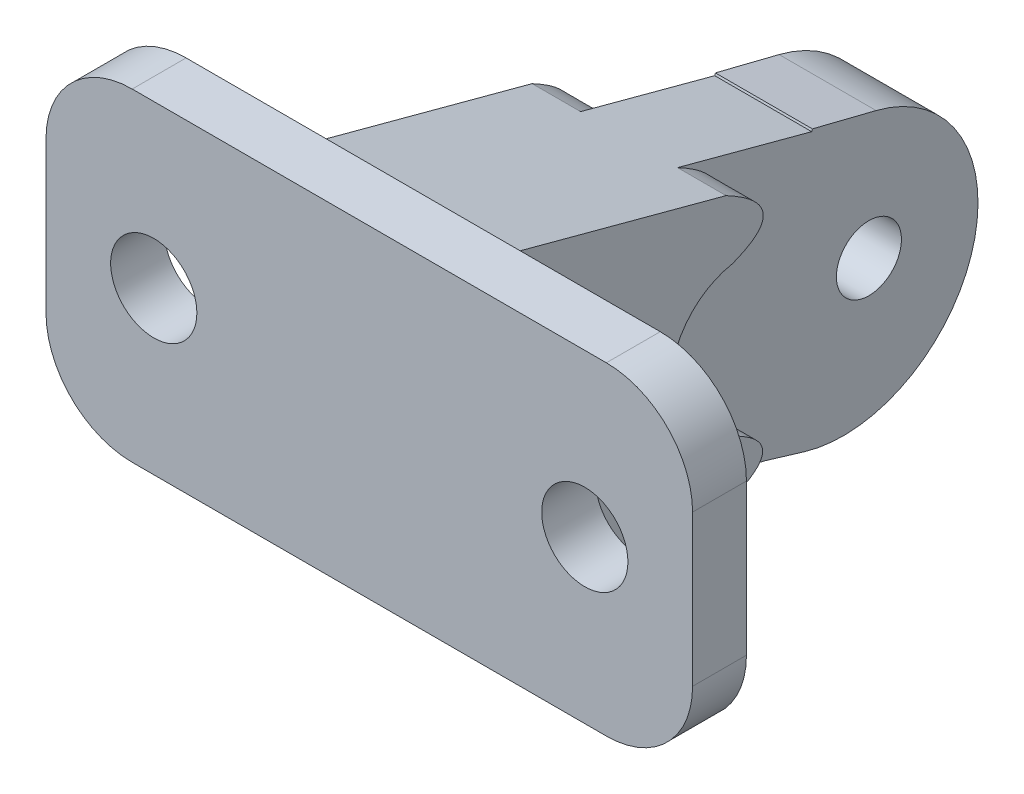
SolidWorks part; units mm, degrees
ref_plane "Front Plane" through (0, 0, 0) normal (0, 0, 1) x (1, 0, 0)
ref_plane "Top Plane" through (0, 0, 0) normal (0, 1, 0) x (1, 0, 0)
ref_plane "Right Plane" through (0, 0, 0) normal (1, 0, 0) x (0, 0, -1)
sketch "Sketch6" plane through (0, 0, 0) normal (0, 0, 1) x (1, 0, 0)
  line L0 (-20, 0) -> (20, 0) construction
  line L1 (-30, 15) -> (30, 15)
  line L2 (-30, 15) -> (-30, -15)
  line L3 (-30, -15) -> (30, -15)
  line L4 (30, 15) -> (30, -15)
  line L5 (-30, 15) -> (30, -15) construction
  line L6 (-30, -15) -> (30, 15) construction
  circle A2 centre (-20, 0) radius 4
  circle A3 centre (20, 0) radius 4
  point P0 (0, 0)
  dimension "D6" = 8
  dimension "D7" = 8
  dimension "D1" = 60
  dimension "D2" = 30
  dimension "D3" = 40
  dimension "D4" = 10
  dimension "D5" = 10
extrude "Boss-Extrude1" add sketch "Sketch6" along normal blind 5
fillet "Fillet3" radius 8 4 edges at (-30, -15, 2.5) (-30, 15, 2.5) (30, -15, 2.5) (30, 15, 2.5)
sketch "Sketch8" plane through (0, 0, 0) normal (0, 0, -1) x (-1, 0, 0)
  line L0 (-22, 15) -> (22, 15) construction
  line L1 (-9, 15) -> (9, 15)
  line L2 (-9, 15) -> (-9, -15)
  line L3 (-9, -15) -> (9, -15)
  line L4 (9, 15) -> (9, -15)
  line L5 (22, -15) -> (-22, -15) construction
  line L6 (-30, -7) -> (-30, 7) construction
  line L7 (30, 7) -> (30, -7) construction
  dimension "D1" = 21
  dimension "D2" = 21
  dimension "D3" = 18
extrude "Boss-Extrude2" add sketch "Sketch8" along normal blind 45
sketch "Sketch10" plane through (-9, 0, 0) normal (-1, 0, 0) x (0, 0, 1)
  line L0 (0, 15) -> (-45, 2.9423)
  line L1 (-45, -15) -> (-45, 15) construction
  line L2 (-45, 2.9423) -> (-45, 15)
  line L3 (-45, 15) -> (0, 15)
  dimension "D1" = 15
extrude "Cut-Extrude1" cut sketch "Sketch10" against normal blind 20
sketch "Sketch13" plane through (-9, 0, 0) normal (-1, 0, 0) x (0, 0, 1)
  line L0 (0, -32.8637) -> (-40, -32.8637) construction
  line L1 (0, -15) -> (0, -38.052) construction
  line L2 (-40, -32.8637) -> (-40, 12.6407) construction
  dimension "D1" = 40
  dimension "D2" = 0
sketch "Sketch15" plane through (-9, 0, 0) normal (-1, 0, 0) x (0, 0, 1)
  line L1 (-20.9686, -10.424) -> (-20.9686, -15) construction
  line L2 (-45, -15) -> (0, -15) construction
  line L3 (-45, 2.9423) -> (0, 15) construction
  line L4 (-19.1059, 9.8806) -> (0, 15)
  line L5 (0, 15) -> (0, -15)
  line L6 (0, -15) -> (-19.1059, -15)
  arc A2 (-18.8147, -9.4319) -> (-19.2388, 4.0114) centre (-20.9686, -2.7715) ccw
  spline S0 degree 2 poles (-19.1059, 9.8806) (-26.0968, 5.898) (-18.824, 3.8919) knots 0 0 0 1 1 1
  spline S1 degree 3 poles (-19.1059, -15) (-23.7374, -13.111) (-23.6404, -11.2549) (-18.8147, -9.4319) knots 0 0 0 0 0.967848 0.967848 0.967848 0.967848
  dimension "D1" = 14
sketch "Sketch17" plane through (-9, 0, 0) normal (-1, 0, 0) x (0, 0, 1)
  line L0 (-19.1059, 9.8806) -> (-33.795, 5.9447)
  line L1 (-45, 2.9423) -> (0, 15) construction
  line L2 (-33.795, 5.9447) -> (-33.1128, -15)
  line L3 (-45, -15) -> (0, -15) construction
  line L4 (-33.1128, -15) -> (-19.1059, -15)
  arc A0 (-19.3961, -9.5926) -> (-19.7213, 4.1165) centre (-20.9686, -2.7715) ccw
  spline S0 degree 2 poles (-19.1059, 9.8806) (-25.6883, 6.3887) (-19.7213, 4.1165) knots 0 0 0 1 1 1
  spline S1 degree 2 poles (-19.3961, -9.5926) (-25.7463, -12.5412) (-19.1059, -15) knots 0 0 0 1 1 1
extrude "Cut-Extrude3" cut sketch "Sketch17" against normal blind 18
sketch "Sketch18" plane through (-9, 0, 0) normal (-1, 0, 0) x (0, 0, 1)
  line L0 (-45, 2.9423) -> (-33.795, 5.9447)
  line L1 (-33.795, 5.9447) -> (-33.1128, -15)
  line L2 (-33.1128, -15) -> (-45, -15)
  line L3 (-45, -15) -> (-45, 2.9423)
extrude "Cut-Extrude4" cut sketch "Sketch18" against normal blind 18
sketch "Sketch20" plane through (-9, 0, 0) normal (-1, 0, 0) x (0, 0, 1)
  line L0 (-37.5314, 5.2543) -> (-25.0542, 8.3871)
  line L2 (-25.0542, 8.3871) -> (-24.5019, -16.9201) construction
  line L3 (-25.0542, 8.3871) -> (-24.5019, -16.9201)
  line L4 (-30.8886, -18.8401) -> (-24.5019, -16.9201)
  arc A2 (-37.5314, 5.2543) -> (-30.8886, -18.8401) centre (-34.4874, -6.8694) ccw
  dimension "D1" = 25
extrude "Boss-Extrude4" add sketch "Sketch20" against normal blind 18 separate body
sketch "Sketch22" plane through (0, -8.7621, 2.6342) normal (0, -0.9577, 0.2879) x (1, 0, 0)
  line L0 (9, -28.3358) -> (-9, -28.3358) construction
  line L1 (-4.5, -28.3358) -> (4.5, -28.3358)
  line L2 (-4.5, -28.3358) -> (-4.5, -51.8819)
  line L3 (-4.5, -51.8819) -> (4.5, -51.8819)
  line L4 (4.5, -28.3358) -> (4.5, -51.8819)
  line L5 (-9, -9.4616) -> (-9, -47.7679) construction
  line L6 (9, -47.5049) -> (9, -34.4296) construction
  dimension "D1" = 4.5
  dimension "D2" = 23.5461
  dimension "D3" = 4.5
extrude "Cut-Extrude5" cut sketch "Sketch22" against normal blind 58 flip side to cut
sketch "Sketch26" plane through (0, 13.9952, -3.75) normal (0, 0.9659, -0.2588) x (1, 0, 0)
  line L0 (-4.5, 34.8927) -> (-4.5, 28.7932) construction
  line L1 (-4.5, 30.7604) -> (4.5, 30.7604)
  line L2 (-4.5, 30.7604) -> (-4.5, 14.0604)
  line L3 (-4.5, 14.0604) -> (4.5, 14.0604)
  line L4 (4.5, 30.7604) -> (4.5, 14.0604)
  dimension "D1" = 9
  dimension "D2" = 16.7
extrude "Boss-Extrude6" add sketch "Sketch26" against normal blind 24.59
sketch "Sketch27" plane through (-4.5, 0, 0) normal (-1, 0, 0) x (0, 0, 1)
  circle A0 centre (-36.8635, -6.2733) radius 3.0173
extrude "Cut-Extrude6" cut sketch "Sketch27" against normal blind 24.59
